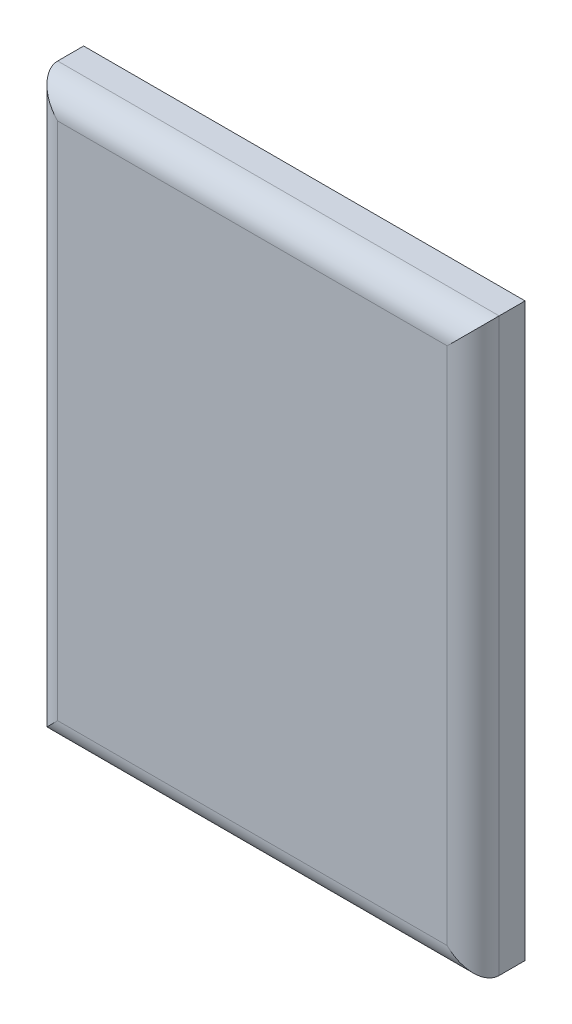
SolidWorks part; units mm, degrees
ref_plane "Front Plane" through (0, 0, 0) normal (0, 0, 1) x (1, 0, 0)
ref_plane "Top Plane" through (0, 0, 0) normal (0, 1, 0) x (1, 0, 0)
ref_plane "Right Plane" through (0, 0, 0) normal (1, 0, 0) x (0, 0, -1)
sketch "Sketch2" plane through (0, 0, 0) normal (0, 0, 1) x (1, 0, 0)
  line L1 (-51.3298, 189.8138) -> (118.6702, 189.8138)
  line L2 (-51.3298, 189.8138) -> (-51.3298, -30.1862)
  line L3 (-51.3298, -30.1862) -> (118.6702, -30.1862)
  line L4 (118.6702, 189.8138) -> (118.6702, -30.1862)
  dimension "D1" = 220
  dimension "D2" = 170
extrude "Boss-Extrude1" add sketch "Sketch2" along normal blind 50
fillet "Fillet1" radius 10 4 edges at (33.6702, 189.8138, 50) (118.6702, 79.8138, 50) (33.6702, -30.1862, 50) (-51.3298, 79.8138, 50)
sketch "Sketch3" plane through (0, 0, 0) normal (0, 0, -1) x (-1, 0, 0)
  line L1 (41.3298, 179.8138) -> (-108.6702, 179.8138)
  line L2 (41.3298, 179.8138) -> (41.3298, -20.1862)
  line L3 (41.3298, -20.1862) -> (-108.6702, -20.1862)
  line L4 (-108.6702, 179.8138) -> (-108.6702, -20.1862)
  dimension "D1" = 10
  dimension "D2" = 10
  dimension "D3" = 10
  dimension "D4" = 10
  dimension "D5" = 10
  dimension "D6" = 10
extrude "Cut-Extrude1" cut sketch "Sketch3" against normal blind 50
ref_plane "Plane1" through (0, 0, 40) normal (0, 0, 1) x (1, 0, 0)
sketch "Sketch6" plane through (0, 0, 40) normal (0, 0, 1) x (1, 0, 0)
  line L0 (-41.3298, 179.8138) -> (-41.3298, -20.1862) construction
  line L1 (-41.3298, 179.8138) -> (108.6702, 179.8138)
  line L2 (-41.3298, 179.8138) -> (-41.3298, -20.1862)
  line L3 (-41.3298, -20.1862) -> (108.6702, -20.1862)
  line L4 (108.6702, 179.8138) -> (108.6702, -20.1862)
  line L5 (108.6702, -20.1862) -> (108.6702, 179.8138) construction
  line L6 (108.6702, -20.1862) -> (118.6702, -30.1862) construction
  line L7 (-41.3298, -20.1862) -> (108.6702, -20.1862) construction
  point P4 (-42.1191, -19.8748)
  point P5 (107.8791, -19.8678)
  point P6 (107.8403, 180.0275)
  point P7 (-41.3298, 179.8138)
  point P10 (108.6702, 179.8138)
  point P13 (108.6702, -20.1862)
  point P18 (-41.3298, -20.1862)
extrude "Boss-Extrude2" add sketch "Sketch6" along normal blind 10
ref_plane "Plane2" through (0, 0, 0) normal (0, 0, 1) x (1, 0, 0)
sketch "Sketch7" plane through (0, 0, 0) normal (0, 0, 1) x (1, 0, 0)
  line L1 (118.6702, 189.8138) -> (-51.3298, 189.8138)
  line L2 (118.6702, 189.8138) -> (118.6702, -30.1862)
  line L3 (118.6702, -30.1862) -> (-51.3298, -30.1862)
  line L4 (-51.3298, 189.8138) -> (-51.3298, -30.1862)
extrude "Cut-Extrude3" cut sketch "Sketch7" along normal blind 30
